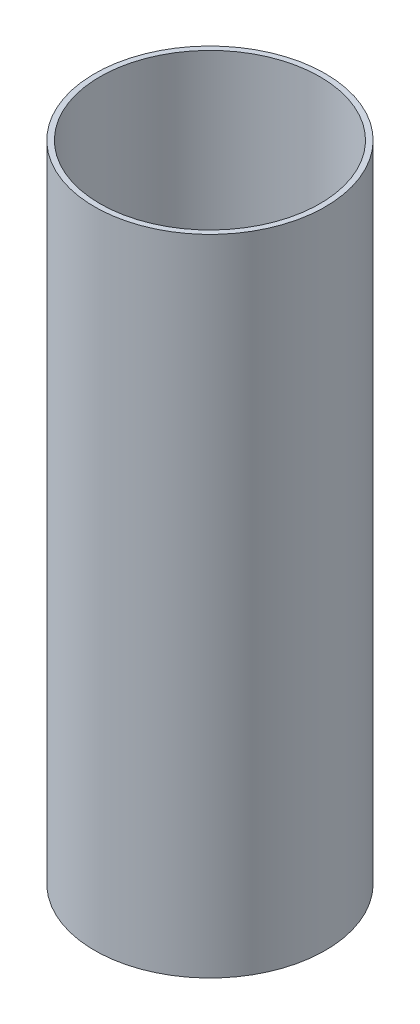
SolidWorks part; units mm, degrees
material "Delrin 2700 NC010, Low Viscosity Acetal Copolymer (SS)"
ref_plane "Front Plane" through (0, 0, 0) normal (0, 0, 1) x (1, 0, 0)
ref_plane "Top Plane" through (0, 0, 0) normal (0, 1, 0) x (1, 0, 0)
ref_plane "Right Plane" through (0, 0, 0) normal (1, 0, 0) x (0, 0, -1)
sketch "Sketch1" plane through (0, 0, 0) normal (0, 0, 1) x (1, 0, 0)
  line L0 (0, 0) -> (0, 190.5) construction
  line L1 (0, 190.5) -> (34.1312, 190.5) construction
  line L2 (34.1312, 190.5) -> (34.1313, 0)
  line L3 (34.1313, 0) -> (0, 0)
  line L4 (34.1312, 190.5) -> (32.5437, 190.5)
  line L5 (32.5437, 190.5) -> (32.5438, 1.5875)
  line L6 (32.5438, 1.5875) -> (0, 1.5875)
  line L7 (0, 1.5875) -> (0, 0)
  dimension "D1" = 1.5875
  dimension "D2" = 1.5875
  dimension "D3" = 32.5437
  dimension "D4" = 190.5
revolve "Revolve1" add sketch "Sketch1" angle 360 about L0
